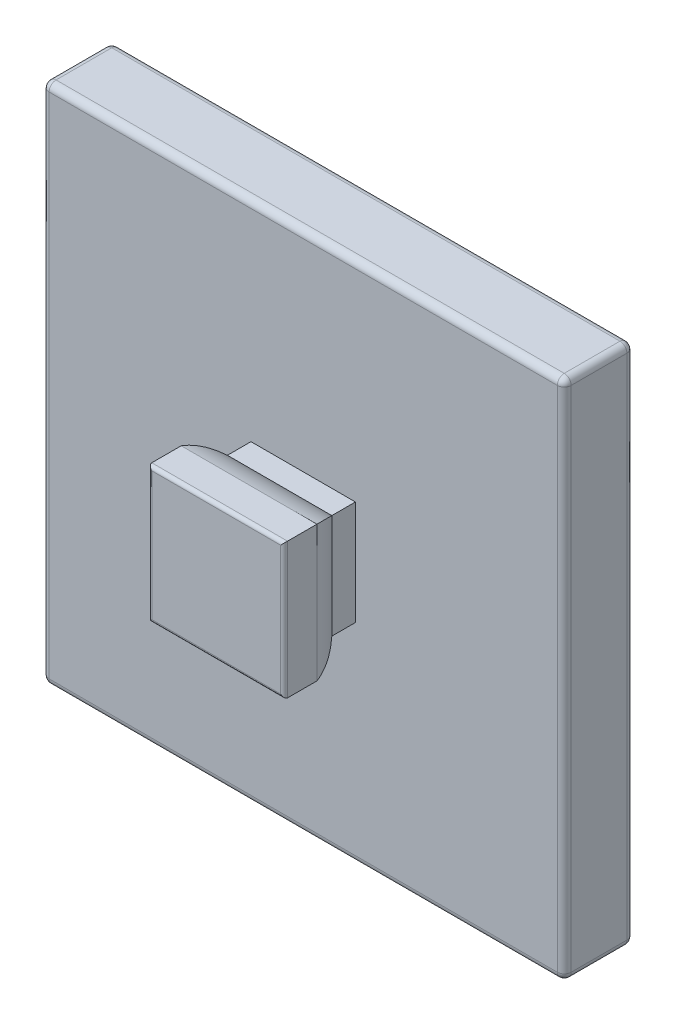
SolidWorks part; units mm, degrees
ref_plane "前视基准面" through (0, 0, 0) normal (0, 0, 1) x (1, 0, 0)
ref_plane "上视基准面" through (0, 0, 0) normal (0, 1, 0) x (1, 0, 0)
ref_plane "右视基准面" through (0, 0, 0) normal (1, 0, 0) x (0, 0, -1)
sketch "草图1" plane through (0, 0, 0) normal (0, 0, 1) x (1, 0, 0)
  line L1 (-7.5, -7.5) -> (7.5, -7.5)
  line L2 (-7.5, -7.5) -> (-7.5, 7.5)
  line L3 (-7.5, 7.5) -> (7.5, 7.5)
  line L4 (7.5, -7.5) -> (7.5, 7.5)
extrude "凸台-拉伸1" add sketch "草图1" against normal blind 2
sketch "草图2" plane through (0, 0, 0) normal (0, 0, 1) x (1, 0, 0)
  line L1 (-1.5, -1.5) -> (1.5, -1.5)
  line L2 (-1.5, -1.5) -> (-1.5, 1.5)
  line L3 (-1.5, 1.5) -> (1.5, 1.5)
  line L4 (1.5, -1.5) -> (1.5, 1.5)
extrude "凸台-拉伸2" add sketch "草图2" along normal blind 1
sketch "草图3" plane through (0, 0, 0) normal (0, 1, 0) x (1, 0, 0)
  line L0 (-1.95, -2.5) -> (1.95, -2.5)
  line L1 (-1.95, -2.5) -> (-1.95, -1.5556)
  line L2 (-1.5, -1) -> (-1.5, 0) construction
  line L3 (-1.5, -0.6771) -> (1.5, -0.6771)
  line L4 (1.95, -2.5) -> (1.95, -1.5556)
  arc A0 (1.95, -1.5556) -> (1.5, -0.6771) centre (0, -2) ccw
  arc A1 (-1.5, -0.6771) -> (-1.95, -1.5556) centre (0, -2) ccw
extrude "凸台-拉伸3" add sketch "草图3" along normal blind 2 and the other way blind 2
sketch "草图4" plane through (0, 0, 0) normal (1, 0, 0) x (0, 0, -1)
  line L0 (-2.5, 1.95) -> (-1.5556, 1.95)
  line L1 (-2.5, 1.95) -> (-2.5, 2)
  line L2 (-2.5, -2) -> (-2.5, 2) construction
  line L3 (-2.5, 2) -> (-0.6771, 2)
  line L4 (-0.6771, 2) -> (-0.6771, 1.5)
  line L5 (-2.5, -2) -> (-0.6771, -2)
  line L6 (-0.6771, -2) -> (-0.6771, -1.5)
  line L7 (-2.5, -1.95) -> (-1.5556, -1.95)
  line L8 (-2.5, -1.95) -> (-2.5, -2)
  arc A0 (-0.6771, 1.5) -> (-1.5556, 1.95) centre (-2, 0) ccw
  arc A2 (-1.5556, -1.95) -> (-0.6771, -1.5) centre (-2, 0) ccw
extrude "切除-拉伸1" cut sketch "草图4" against normal up to next and the other way up to next
fillet "圆角1" radius 0.1 4 edges at (0, -1.95, 2.5) (-1.95, 0, 2.5) (0, 1.95, 2.5) (1.95, 0, 2.5)
fillet "圆角2" radius 0.2 12 edges at (0, -7.5, -2) (0, -7.5, 0) (-7.5, -7.5, -1) (-7.5, 0, -2) (-7.5, 0, 0) (-7.5, 7.5, -1) (0, 7.5, -2) (0, 7.5, 0) (7.5, 7.5, -1) (7.5, 0, -2) (7.5, -7.5, -1) (7.5, 0, 0)
